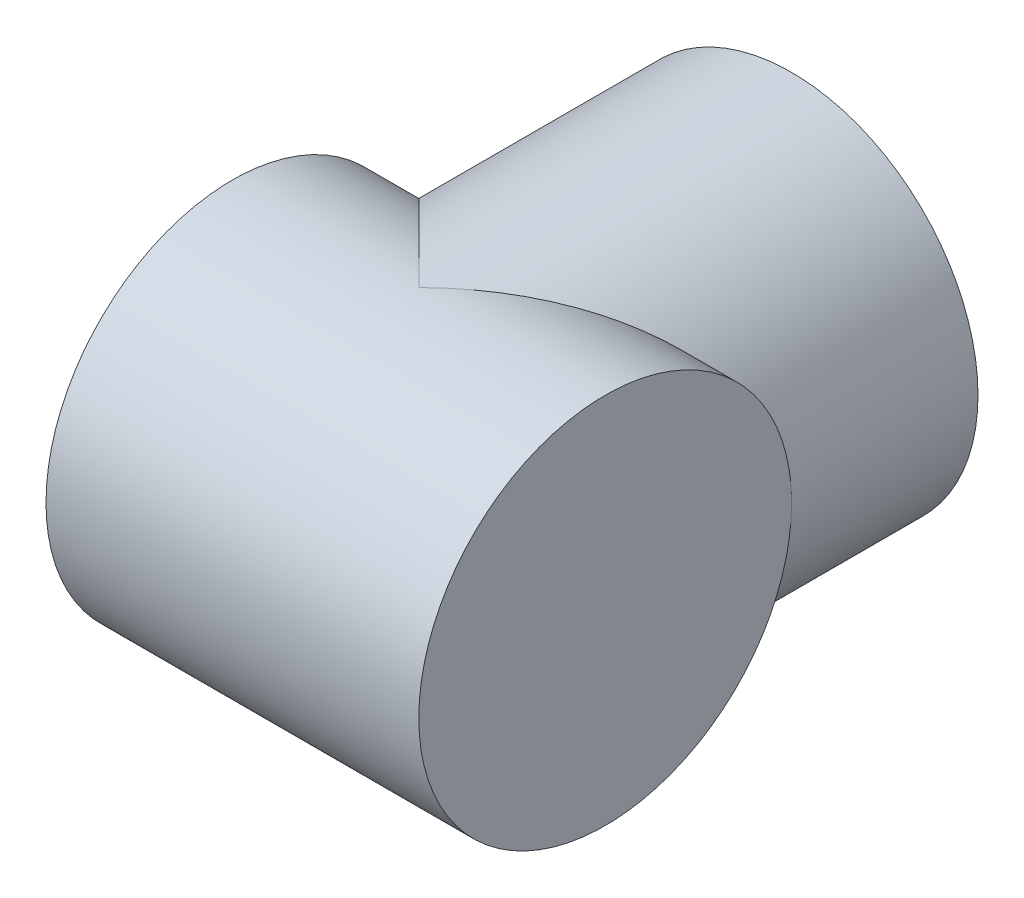
SolidWorks part; units mm, degrees
ref_plane "前视基准面" through (0, 0, 0) normal (0, 0, 1) x (1, 0, 0)
ref_plane "上视基准面" through (0, 0, 0) normal (0, 1, 0) x (1, 0, 0)
ref_plane "右视基准面" through (0, 0, 0) normal (1, 0, 0) x (0, 0, -1)
sketch "草图1" plane through (0, 0, 0) normal (1, 0, 0) x (0, 0, -1)
  circle A0 centre (0, 0) radius 150
extrude "凸台-拉伸1" add sketch "草图1" along normal mid plane 300
sketch "草图2" plane through (0, 0, 0) normal (0, 0, 1) x (1, 0, 0)
  circle A0 centre (0, 0) radius 150
extrude "凸台-拉伸2" add sketch "草图2" against normal blind 300
